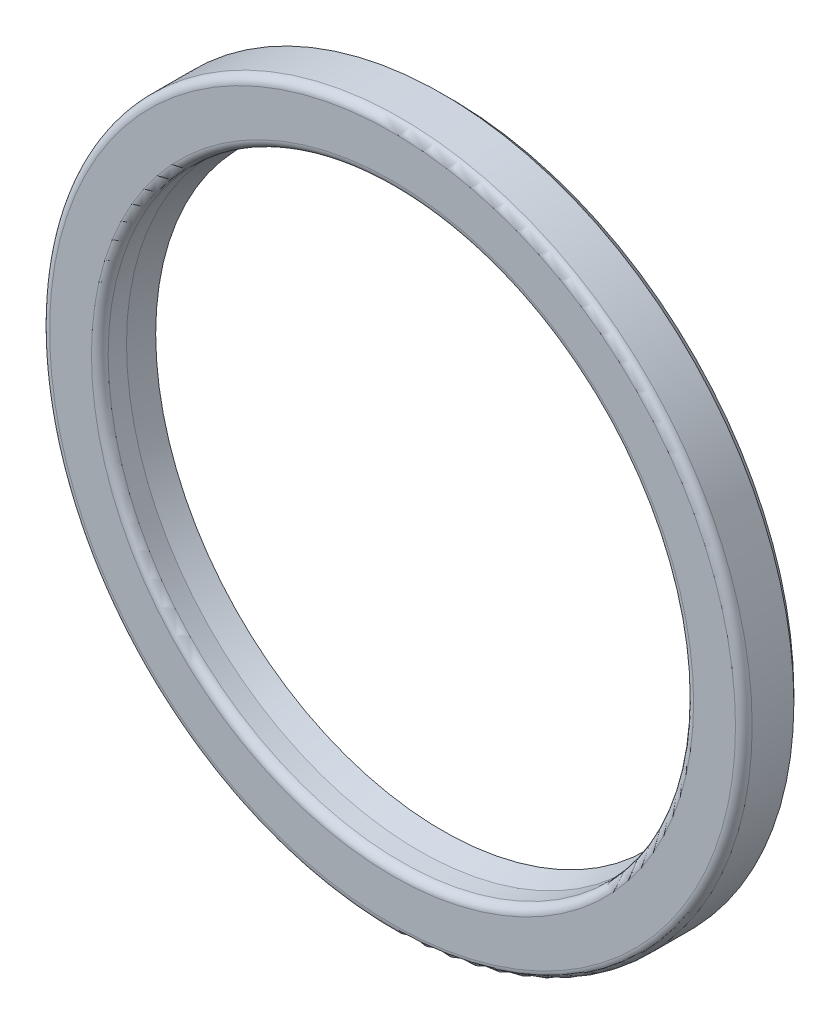
SolidWorks part; units mm, degrees
material "O-Ring"
ref_plane "Front Plane" through (0, 0, 0) normal (0, 0, 1) x (1, 0, 0)
ref_plane "Top Plane" through (0, 0, 0) normal (0, 1, 0) x (1, 0, 0)
ref_plane "Right Plane" through (0, 0, 0) normal (1, 0, 0) x (0, 0, -1)
sketch "Sketch1" plane through (0, 0, 0) normal (1, 0, 0) x (0, 0, -1)
  line L0 (0, 18.05) -> (0, 20.56)
  line L1 (0.5, 21.06) -> (3, 21.06)
  line L2 (3.5, 18.3) -> (0.5, 19.4)
  line L3 (3, 21.06) -> (3.5, 20.56)
  line L4 (0.5, 19.4) -> (0.5, 20.4)
  line L5 (3.5, 20.4) -> (0.5, 20.4)
  line L7 (1.6, 17.55) -> (0.5, 17.55)
  line L8 (0, 0) -> (11.0087, 0) construction
  line L10 (3.5, 20.56) -> (3.5, 20.4)
  line L11 (3.5, 18) -> (3, 17.2)
  line L12 (3, 17.2) -> (1.6, 17.55)
  line L13 (3.5, 18.3) -> (3.5, 18)
  arc A2 (0, 20.56) -> (0.5, 21.06) centre (0.5, 20.56) cw
  arc A3 (0.5, 17.55) -> (0, 18.05) centre (0.5, 18.05) cw
  dimension "D8" = 0.5
  dimension "D9" = 40.8
  dimension "D19" = 0.5
  dimension "D12" = 38.8
  dimension "D14" = 1.6
  dimension "D2" = 42.12
  dimension "D3" = 35.1
  dimension "D4" = 34.4
  dimension "D5" = 45
  dimension "D6" = 0.5
  dimension "D7" = 3.5
  dimension "D10" = 3
  dimension "D11" = 36.6
  dimension "D13" = 36
revolve "Revolve1" add sketch "Sketch1" angle 360 about L8
